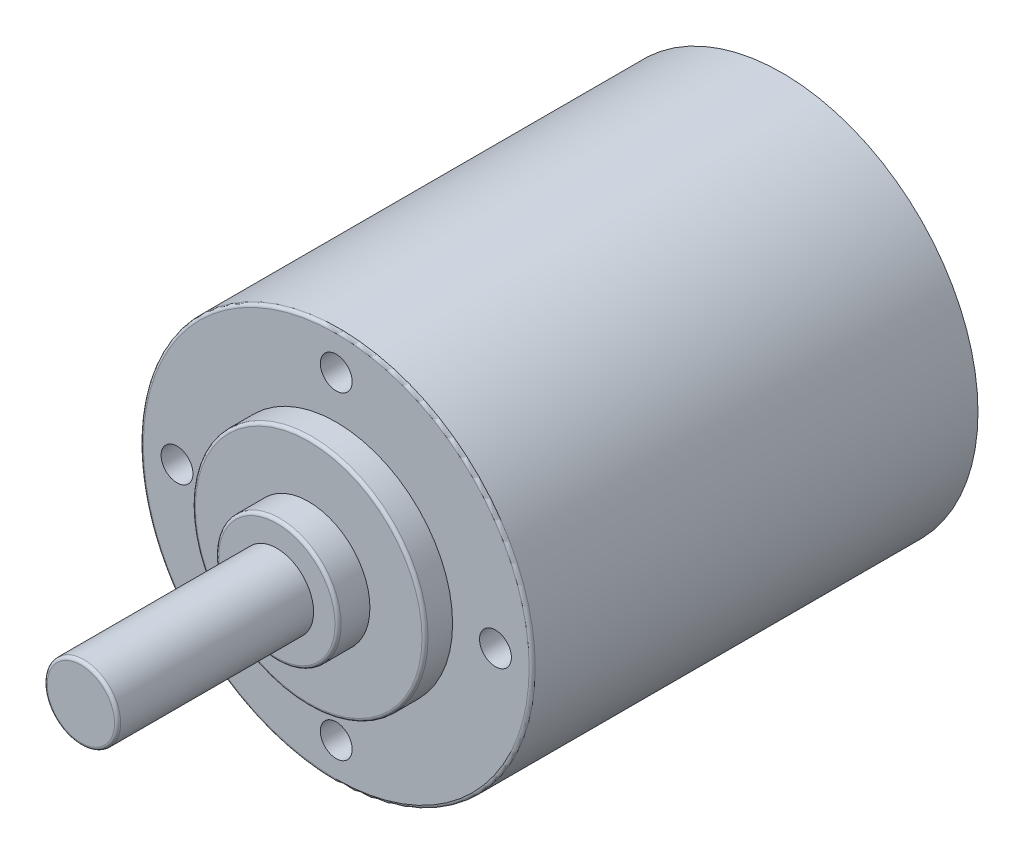
SolidWorks part; units mm, degrees
ref_plane "Plan de face" through (0, 0, 0) normal (0, 0, 1) x (1, 0, 0)
ref_plane "Plan de dessus" through (0, 0, 0) normal (0, 1, 0) x (1, 0, 0)
ref_plane "Plan de droite" through (0, 0, 0) normal (1, 0, 0) x (0, 0, -1)
sketch "Esquisse1" plane through (0, 0, 0) normal (0, 0, 1) x (1, 0, 0)
  circle A0 centre (0, 0) radius 16
  dimension "D1" = 32
extrude "Boss.-Extru.1" add sketch "Esquisse1" along normal blind 36.4
sketch "Esquisse2" plane through (0, 0, 36.4) normal (0, 0, 1) x (1, 0, 0)
  circle A0 centre (0, 0) radius 9.5
  dimension "D1" = 19
extrude "Boss.-Extru.2" add sketch "Esquisse2" along normal blind 2.25
sketch "Esquisse3" plane through (0, 0, 38.65) normal (0, 0, 1) x (1, 0, 0)
  circle A0 centre (0, 0) radius 5
extrude "Boss.-Extru.3" add sketch "Esquisse3" along normal blind 2.6
sketch "Esquisse4" plane through (0, 0, 41.25) normal (0, 0, 1) x (1, 0, 0)
  circle A0 centre (0, 0) radius 3
extrude "Boss.-Extru.4" add sketch "Esquisse4" along normal blind 16
fillet "Congé1" radius 0.25 4 edges at (16, 0, 36.4) (9.5, 0, 38.65) (3, 0, 57.25) (5, 0, 41.25)
sketch "Esquisse6" plane through (0, 0, 36.4) normal (0, 0, 1) x (1, 0, 0)
  circle A0 centre (0, 0) radius 13 construction
  circle A1 centre (0, 13) radius 1.3
  circle A2 centre (-13, 0) radius 1.3
  circle A3 centre (13, 0) radius 1.3
  circle A4 centre (0, -13) radius 1.3
extrude "Enlèv. mat.-Extru.1" cut sketch "Esquisse6" against normal blind 7
sketch "Esquisse7" plane through (0, 0, 0) normal (0, 0, -1) x (-1, 0, 0)
  circle A0 centre (0, 0) radius 2
extrude "Enlèv. mat.-Extru.2" cut sketch "Esquisse7" against normal blind 13.8
